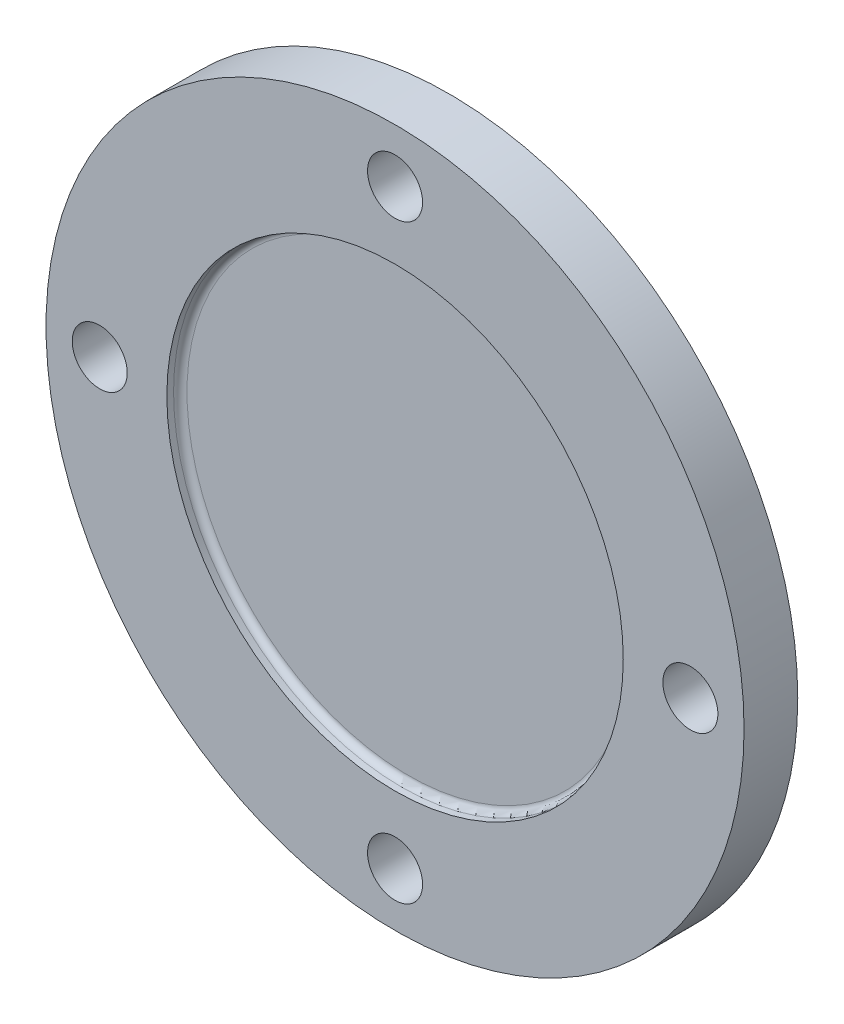
SolidWorks part; units mm, degrees
ref_plane "Спереди" through (0, 0, 0) normal (0, 0, 1) x (1, 0, 0)
ref_plane "Сверху" through (0, 0, 0) normal (0, 1, 0) x (1, 0, 0)
ref_plane "Справа" through (0, 0, 0) normal (1, 0, 0) x (0, 0, -1)
sketch "Эскиз1" plane through (0, 0, 0) normal (0, 0, 1) x (1, 0, 0)
  circle A0 centre (0, 0) radius 52
  circle A2 centre (0, 44) radius 4.1
  circle A6 centre (44, 0) radius 4.1
  circle A7 centre (0, -44) radius 4.1
  circle A8 centre (-44, 0) radius 4.1
  point P14 (0, 0)
  dimension "D1" = 104
  dimension "D2" = 8.2
  dimension "D4" = 44
  dimension "D3" = 4
extrude "Бобышка-Вытянуть1" add sketch "Эскиз1" along normal blind 8
sketch "Эскиз2" plane through (0, 0, 8) normal (0, 0, 1) x (1, 0, 0)
  circle A0 centre (0, 0) radius 34
  dimension "D1" = 68
extrude "Вырез-Вытянуть1" cut sketch "Эскиз2" against normal blind 2
fillet "Скругление1" radius 1 1 edges at (34, 0, 6)
sketch "Эскиз3" plane through (0, 0, 0) normal (0, 0, -1) x (-1, 0, 0)
  circle A0 centre (0, 0) radius 34
  circle A1 centre (0, 0) radius 25
  dimension "D1" = 68
  dimension "D2" = 50
extrude "Бобышка-Вытянуть2" add sketch "Эскиз3" along normal blind 11.3
fillet "Скругление2" radius 6 1 edges at (-25, 0, 0)
